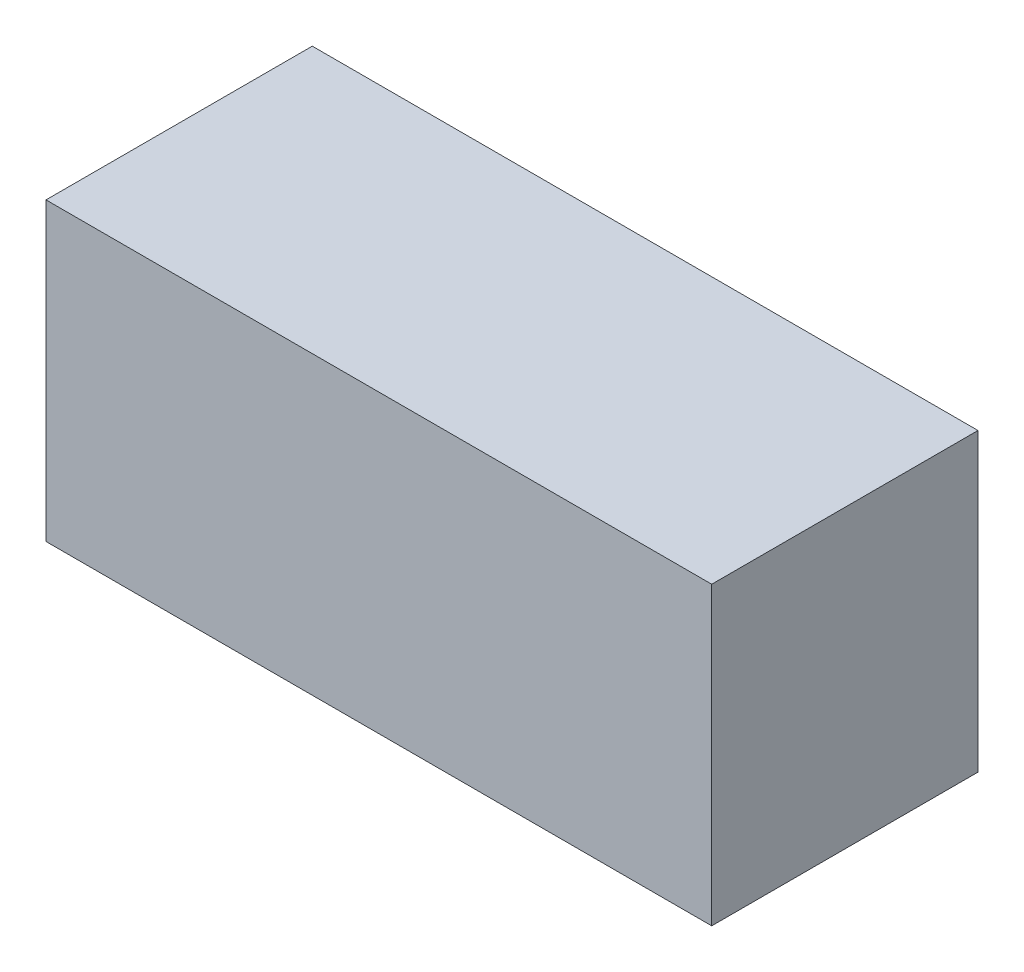
SolidWorks part; units mm, degrees
ref_plane "前视基准面" through (0, 0, 0) normal (0, 0, 1) x (1, 0, 0)
ref_plane "上视基准面" through (0, 0, 0) normal (0, 1, 0) x (1, 0, 0)
ref_plane "右视基准面" through (0, 0, 0) normal (1, 0, 0) x (0, 0, -1)
sketch "草图1" plane through (0, 0, 0) normal (0, 0, 1) x (1, 0, 0)
  line L1 (-225, 100) -> (225, 100)
  line L2 (-225, 100) -> (-225, -100)
  line L3 (-225, -100) -> (225, -100)
  line L4 (225, 100) -> (225, -100)
  line L5 (-225, 100) -> (225, -100) construction
  line L6 (-225, -100) -> (225, 100) construction
  point P0 (0, 0)
  dimension "D1" = 450
  dimension "D2" = 200
extrude "凸台-拉伸1" add sketch "草图1" along normal blind 180
